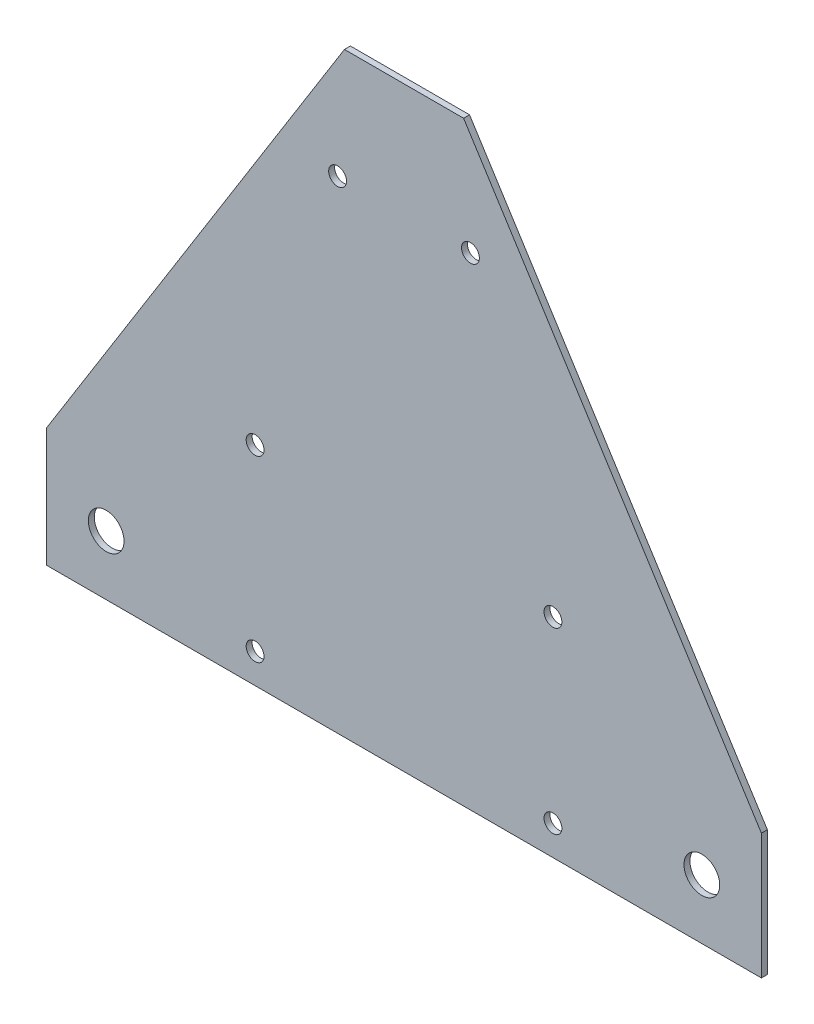
SolidWorks part; units mm, degrees
ref_plane "前视基准面" through (0, 0, 0) normal (0, 0, 1) x (1, 0, 0)
ref_plane "上视基准面" through (0, 0, 0) normal (0, 1, 0) x (1, 0, 0)
ref_plane "右视基准面" through (0, 0, 0) normal (1, 0, 0) x (0, 0, -1)
sketch "草图1" plane through (0, 0, 0) normal (0, 0, 1) x (1, 0, 0)
  line L1 (-10, 50.1092) -> (10, 50.1092)
  line L2 (-60, -29.8908) -> (-60, -49.8908)
  line L3 (-60, -49.8908) -> (60, -49.8908)
  line L4 (60, -28.8382) -> (60, -49.8908)
  line L6 (-10, 50.1092) -> (10, 50.1092)
  line L14 (-60, -29.8908) -> (-60, -49.8908)
  line L15 (-60, -49.8908) -> (-40, -49.8908)
  line L21 (40, -49.8908) -> (60, -49.8908)
  line L22 (60, -28.8382) -> (60, -49.8908)
  line L26 (-10, 50.1092) -> (-60, -29.8908)
  line L27 (10, 50.1092) -> (60, -28.8382)
  circle A0 centre (-50, -39.8908) radius 3
  circle A1 centre (50, -39.8908) radius 3
  point P0 (0, 0)
  point P5 (0, 35.1092)
  point P18 (0, 35)
  dimension "D7" = 10
  dimension "D5" = 60
  dimension "D6" = 15
  dimension "D8" = 10
  dimension "D9" = 10
  dimension "D10" = 10
extrude "凸台-拉伸2" add sketch "草图1" along normal blind 1
sketch "草图3" plane through (0, 0, 1) normal (0, 0, 1) x (1, 0, 0)
  line L0 (-10, 50.1092) -> (10, 50.1092) construction
  circle A0 centre (-11.15, 31.1092) radius 1.5
  circle A1 centre (11.15, 31.1092) radius 1.5
  dimension "D1" = 19
  dimension "D2" = 19
extrude "切除-拉伸1" cut sketch "草图3" against normal blind 10
sketch "草图5" plane through (0, 0, 1) normal (0, 0, 1) x (1, 0, 0)
  line L0 (-60, -49.8908) -> (60, -49.8908) construction
  line L1 (60, -28.8382) -> (60, -49.8908) construction
  circle A0 centre (25, -14.8908) radius 1.5
  circle A1 centre (25, -44.8908) radius 1.5
  circle A2 centre (-25, -44.8908) radius 1.5
  circle A3 centre (-25, -14.8908) radius 1.5
  dimension "D1" = 35
  dimension "D3" = 35
  dimension "D2" = 35
  dimension "D4" = 5
extrude "切除-拉伸2" cut sketch "草图5" against normal blind 1
